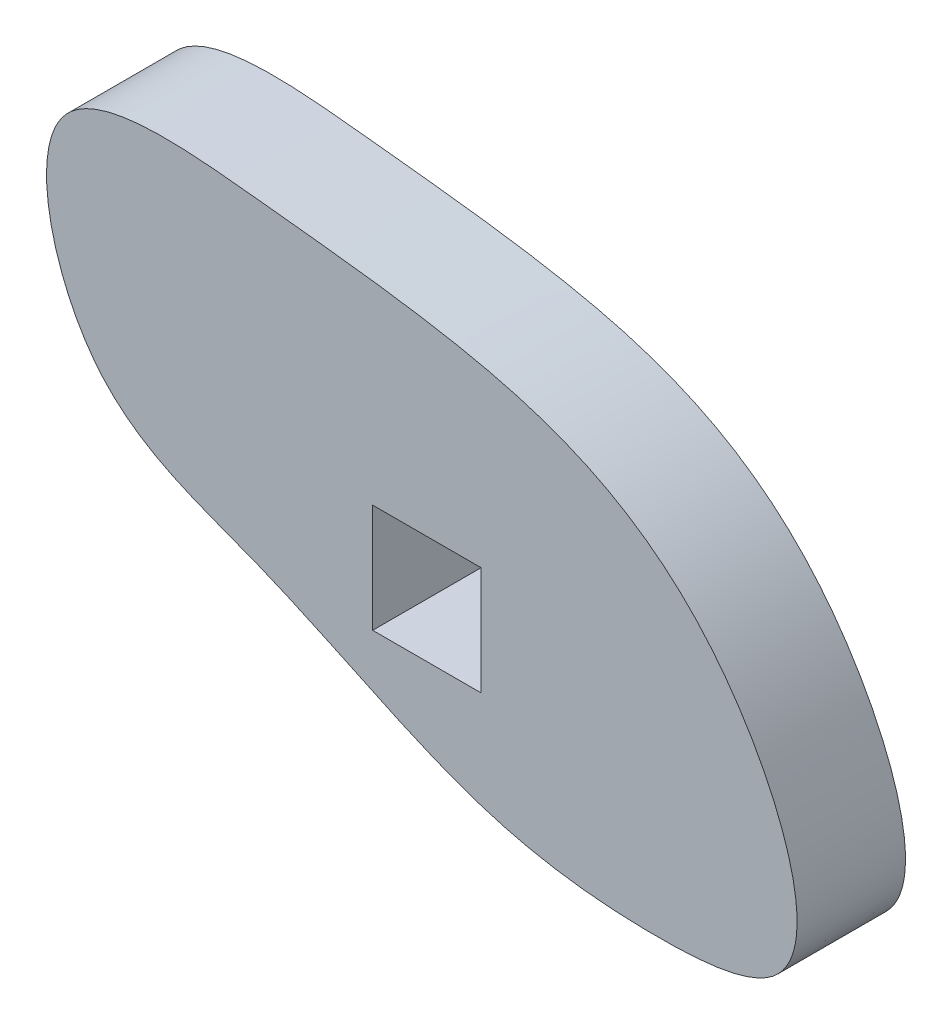
SolidWorks part; units mm, degrees
ref_plane "Front Plane" through (0, 0, 0) normal (0, 0, 1) x (1, 0, 0)
ref_plane "Top Plane" through (0, 0, 0) normal (0, 1, 0) x (1, 0, 0)
ref_plane "Right Plane" through (0, 0, 0) normal (1, 0, 0) x (0, 0, -1)
sketch "Sketch1" plane through (0, 0, 0) normal (0, 0, 1) x (1, 0, 0)
  line L0 (7.7882, 62.5332) -> (6.2642, 62.5332)
  line L1 (7.7882, 62.5332) -> (7.7882, 61.0092)
  line L2 (7.7882, 61.0092) -> (6.2642, 61.0092)
  line L3 (6.2642, 62.5332) -> (6.2642, 61.0092)
  spline S0 degree 3 poles (4.9532, 61.0216) (7.4643, 59.5451) (9.8711, 59.2065) (12.9933, 59.4291) (11.1453, 64.0958) (7.7683, 65.1209) (4.8103, 65.4252) (1.1089, 65.839) (2.0429, 61.8155) (4.9532, 61.0216) (7.4643, 59.5451) (9.8711, 59.2065) knots -0.336718 -0.22814 -0.130925 0 0.094465 0.158663 0.295652 0.457811 0.557025 0.663282 0.77186 0.869075 1 1.094465 1.158663 1.295652 only from (7.7882, 59.6374) to (7.7882, 59.6374)
  dimension "D1" = 1.524
  dimension "D2" = 1.524
extrude "Boss-Extrude1" add sketch "Sketch1" along normal blind 1.524
